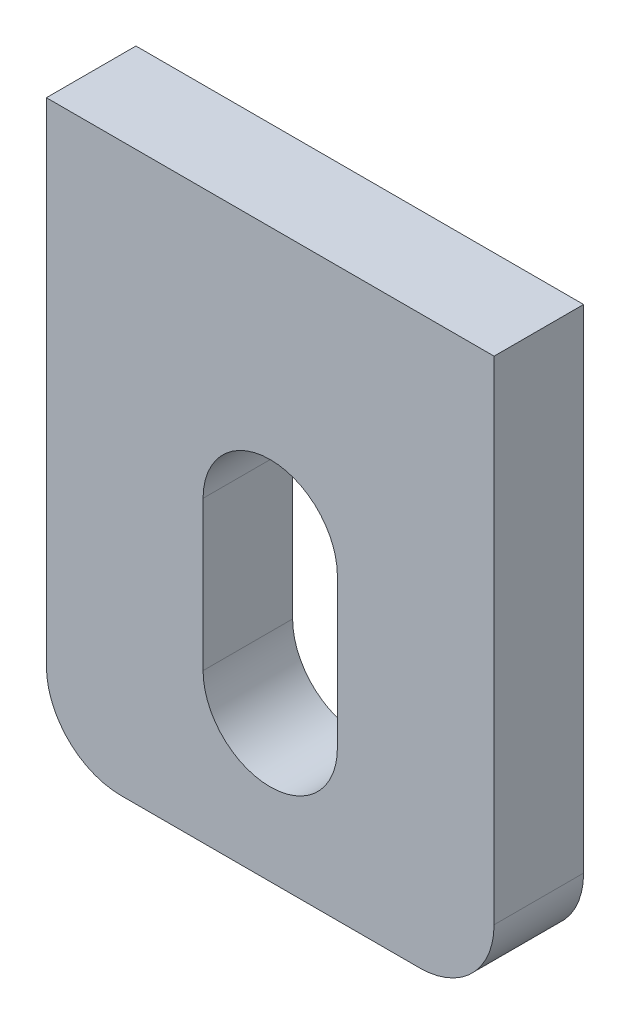
SolidWorks part; units mm, degrees
material "Q355"
ref_plane "前视基准面" through (0, 0, 0) normal (0, 0, 1) x (1, 0, 0)
ref_plane "上视基准面" through (0, 0, 0) normal (0, 1, 0) x (1, 0, 0)
ref_plane "右视基准面" through (0, 0, 0) normal (1, 0, 0) x (0, 0, -1)
sketch "草图1" plane through (0, 0, 0) normal (0, 0, 1) x (1, 0, 0)
  line L0 (15, 38) -> (15, 0) construction
  line L1 (0, 0) -> (30, 0)
  line L2 (0, 0) -> (0, 38)
  line L3 (0, 38) -> (30, 38)
  line L4 (30, 0) -> (30, 38)
  line L5 (15, 20) -> (15, 10) construction
  line L6 (19.5, 20) -> (19.5, 10)
  line L7 (10.5, 20) -> (10.5, 10)
  arc A0 (19.5, 20) -> (10.5, 20) centre (15, 20) ccw
  arc A1 (10.5, 10) -> (19.5, 10) centre (15, 10) ccw
  point P9 (15, 15)
  dimension "D3" = 4.5
  dimension "D1" = 30
  dimension "D2" = 38
  dimension "D4" = 10
  dimension "D5" = 10
extrude "凸台-拉伸1" add sketch "草图1" along normal blind 6
fillet "圆角1" radius 5 2 edges at (30, 0, 3) (0, 0, 3)
